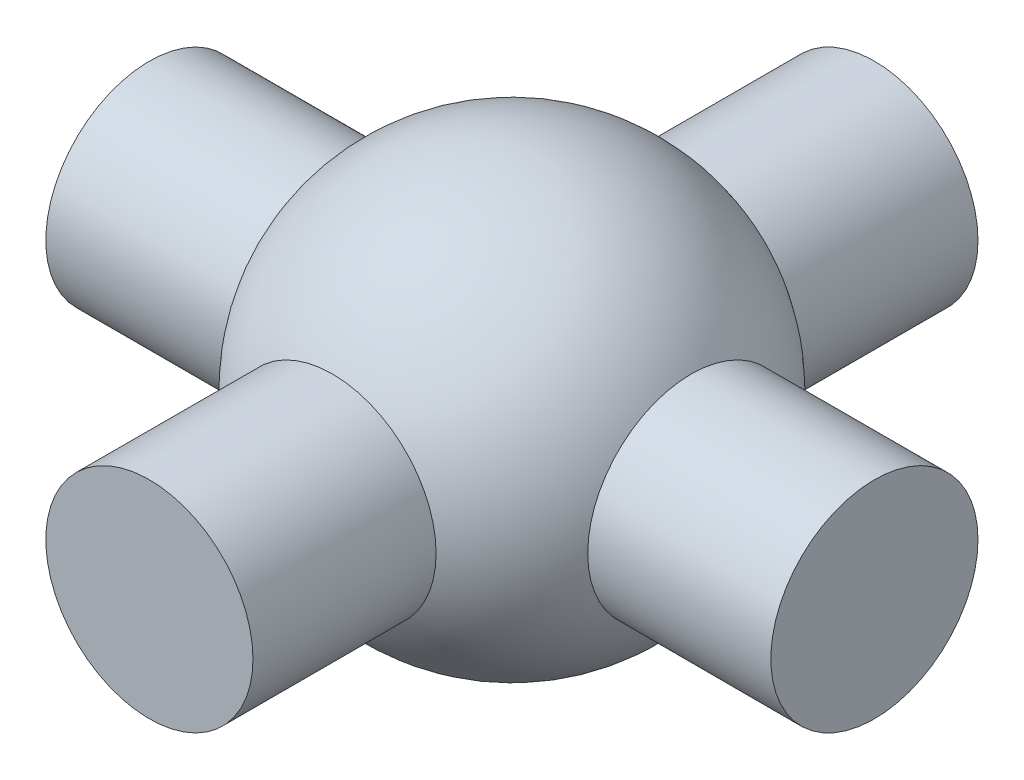
SolidWorks part; units mm, degrees
ref_plane "Front Plane" through (0, 0, 0) normal (0, 0, 1) x (1, 0, 0)
ref_plane "Top Plane" through (0, 0, 0) normal (0, 1, 0) x (1, 0, 0)
ref_plane "Right Plane" through (0, 0, 0) normal (1, 0, 0) x (0, 0, -1)
sketch "Sketch1" plane through (0, 0, 0) normal (0, 1, 0) x (1, 0, 0)
  line L0 (0, 20) -> (0, -20)
  arc A1 (0, 20) -> (0, -20) centre (0, 0) ccw
  dimension "D1" = 40
revolve "Revolve1" add sketch "Sketch1" angle 360 about L0
sketch "Sketch2" plane through (0, 0, 0) normal (0, 0, 1) x (1, 0, 0)
  circle A0 centre (0, 0) radius 10
  dimension "20" = 20
extrude "Boss-Extrude1" add sketch "Sketch2" along normal mid plane 70 separate body
sketch "Sketch3" plane through (0, 0, 0) normal (1, 0, 0) x (0, 0, -1)
  circle A0 centre (0, 0) radius 10
  dimension "D1" = 20
extrude "Boss-Extrude2" add sketch "Sketch3" along normal mid plane 70
